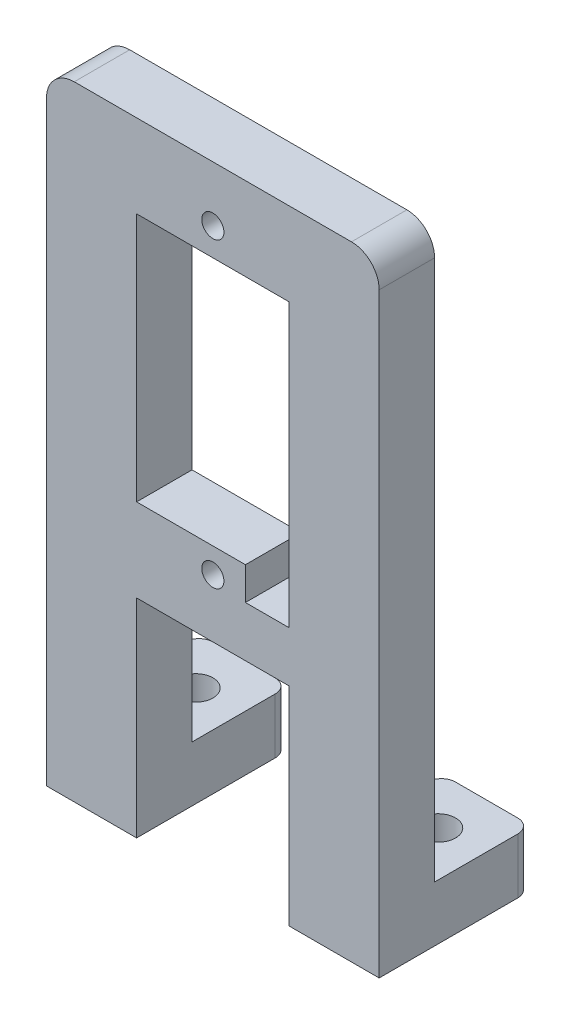
SolidWorks part; units mm, degrees
ref_plane "Front Plane" through (0, 0, 0) normal (0, 0, 1) x (1, 0, 0)
ref_plane "Top Plane" through (0, 0, 0) normal (0, 1, 0) x (1, 0, 0)
ref_plane "Right Plane" through (0, 0, 0) normal (1, 0, 0) x (0, 0, -1)
sketch "Sketch1" plane through (0, 0, 0) normal (0, 0, 1) x (1, 0, 0)
  line L0 (-15.24, -19.05) -> (-15.24, -38.1)
  line L1 (-6.985, 11.43) -> (6.985, 11.43)
  line L2 (-6.985, 11.43) -> (-6.985, -11.43)
  line L3 (-6.985, -11.43) -> (6.985, -11.43)
  line L4 (6.985, 11.43) -> (6.985, -11.43)
  line L5 (-15.24, 19.05) -> (15.24, 19.05)
  line L6 (-15.24, 19.05) -> (-15.24, -19.05)
  line L7 (-15.24, -19.05) -> (15.24, -19.05)
  line L8 (15.24, 19.05) -> (15.24, -19.05)
  line L9 (-15.24, -38.1) -> (-6.985, -38.1)
  line L10 (-6.985, -38.1) -> (-6.985, -19.05)
  line L11 (-15.24, -19.05) -> (-6.985, -19.05)
  line L12 (15.24, -19.05) -> (15.24, -38.1)
  line L13 (15.24, -38.1) -> (6.985, -38.1)
  line L14 (6.985, -38.1) -> (6.985, -19.05)
  line L15 (6.985, -19.05) -> (15.24, -19.05)
  point P5 (0, 11.43)
  point P6 (-6.985, 0)
  point P12 (0, 19.05)
  point P13 (-15.24, 0)
  dimension "D1" = 13.97
  dimension "D2" = 22.86
  dimension "D3" = 30.48
  dimension "D4" = 38.1
  dimension "D5" = 19.05
extrude "Boss-Extrude1" add sketch "Sketch1" along normal blind 5.08 contours L6 L5 L8 L7 | L11 L10 L9 L0 | L12 L13 L14 L15 | L2 L1 L4 L3
fillet "Fillet1" radius 2.54 2 edges at (15.24, 19.05, 2.54) (-15.24, 19.05, 2.54)
ref_plane "Plane1" through (0, -38.1, 0) normal (0, 1, 0) x (1, 0, 0)
sketch "Sketch3" plane through (0, -38.1, 0) normal (0, 1, 0) x (1, 0, 0)
  line L0 (-15.24, 0) -> (-15.24, 8.89)
  line L1 (-15.24, 8.89) -> (-6.985, 8.89)
  line L2 (-6.985, 8.89) -> (-6.985, 0)
  line L3 (-12.7, 0) -> (12.7, 0) construction
  line L4 (-6.985, 0) -> (-15.24, 0)
  line L5 (-15.24, 0) -> (-6.985, 0) construction
  dimension "D2" = 8.89
extrude "Boss-Extrude2" add sketch "Sketch3" along normal blind 5.08
sketch "Sketch5" plane through (0, 0, 5.08) normal (0, 0, 1) x (1, 0, 0)
  line L2 (-6.985, 11.43) -> (6.985, 11.43) construction
  circle A0 centre (0, 13.97) radius 1.016
  circle A1 centre (0, -13.716) radius 1.016
  dimension "D1" = 2.032
  dimension "D2" = 2.032
  dimension "D3" = 27.686
  dimension "D4" = 2.54
extrude "Cut-Extrude1" cut sketch "Sketch5" against normal blind 5.08
sketch "Sketch6" plane through (0, -33.02, 0) normal (0, 1, 0) x (1, 0, 0)
  line L0 (-15.24, 8.89) -> (-15.24, 0) construction
  line L1 (-6.985, 8.89) -> (-15.24, 8.89) construction
  circle A0 centre (-11.1125, 4.445) radius 1.6
  point P4 (-15.24, 4.445)
  point P7 (-11.1125, 8.89)
  dimension "D1" = 3.2
extrude "Cut-Extrude2" cut sketch "Sketch6" against normal blind 5.08
mirror "Mirror2" about plane through (0, 0, 0) normal (1, 0, 0) of "Cut-Extrude2", "Boss-Extrude2"
fillet "Fillet2" radius 1.27 4 edges at (-6.985, -35.56, -8.89) (6.985, -35.56, -8.89) (15.24, -35.56, -8.89) (-15.24, -35.56, -8.89)
sketch "Sketch7" plane through (0, 0, 5.08) normal (0, 0, 1) x (1, 0, 0)
  line L0 (6.985, -11.43) -> (6.985, -14.43)
  line L1 (6.985, -14.43) -> (2.985, -14.43)
  line L2 (2.985, -14.43) -> (2.985, -11.43)
  line L3 (-6.985, -11.43) -> (6.985, -11.43) construction
  line L4 (2.985, -11.43) -> (6.985, -11.43)
  dimension "D1" = 4
  dimension "D2" = 3
extrude "Cut-Extrude3" cut sketch "Sketch7" against normal through all
